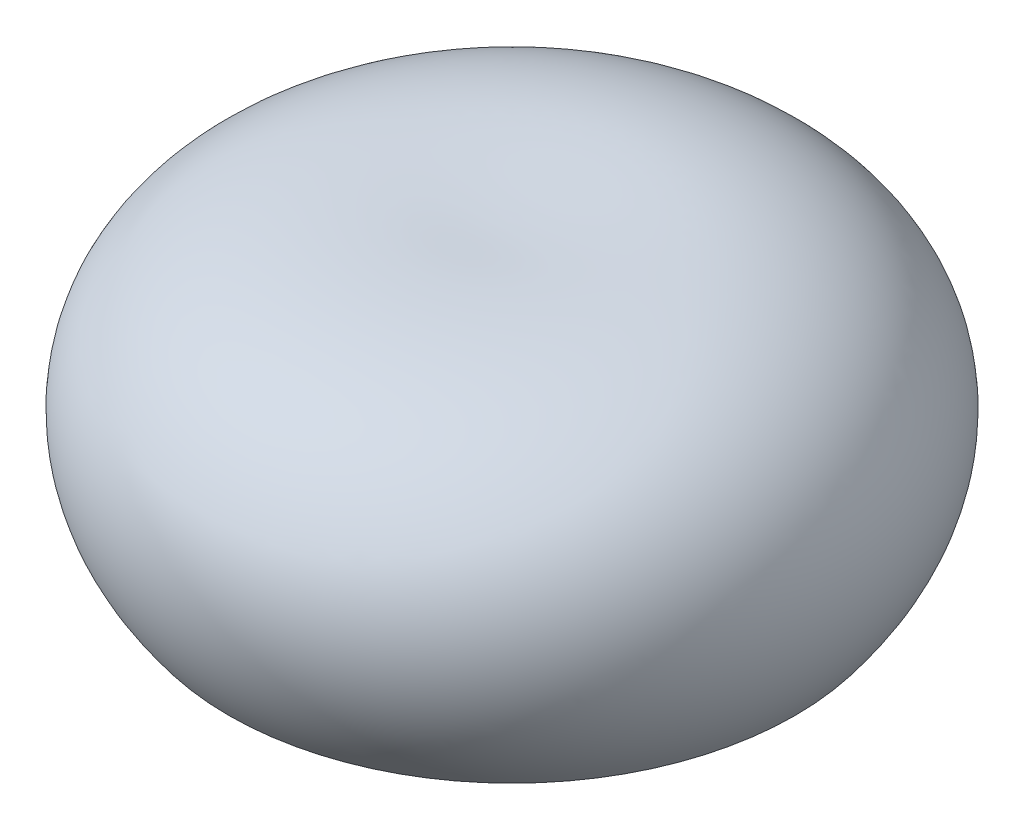
SolidWorks part; units mm, degrees
ref_plane "前视基准面" through (0, 0, 0) normal (0, 0, 1) x (1, 0, 0)
ref_plane "上视基准面" through (0, 0, 0) normal (0, 1, 0) x (1, 0, 0)
ref_plane "右视基准面" through (0, 0, 0) normal (1, 0, 0) x (0, 0, -1)
curve "曲线1"
  spline degree 3 poles (0, 7, 0) (0.0738, 6.9996, 0) (0.1783, 6.9991, 0) (0.3064, 7.0012, 0) (0.3805, 7.0029, 0) (0.4416, 7.0045, 0) (0.495, 7.0061, 0) (0.5432, 7.0077, 0) (0.5875, 7.0093, 0) (0.6288, 7.0109, 0) (0.6676, 7.0125, 0) (0.7044, 7.0141, 0) (0.7394, 7.0157, 0) (0.7729, 7.0172, 0) (0.8051, 7.0187, 0) (0.8362, 7.0203, 0) (0.8662, 7.0218, 0) (0.8953, 7.0233, 0) (0.9235, 7.0247, 0) (0.951, 7.0262, 0) (0.9778, 7.0276, 0) (1.004, 7.0291, 0) (1.0295, 7.0305, 0) (1.0545, 7.0319, 0) (1.079, 7.0333, 0) (1.103, 7.0346, 0) (1.1265, 7.036, 0) (1.1496, 7.0373, 0) (1.1724, 7.0386, 0) (1.1947, 7.0399, 0) (1.2167, 7.0412, 0) (1.2384, 7.0425, 0) (1.2598, 7.0438, 0) (1.2808, 7.045, 0) (1.3016, 7.0462, 0) (1.3221, 7.0474, 0) (1.3423, 7.0486, 0) (1.3623, 7.0498, 0) (1.382, 7.051, 0) (1.4015, 7.0521, 0) (1.4208, 7.0533, 0) (1.4399, 7.0544, 0) (1.4588, 7.0555, 0) (1.4775, 7.0566, 0) (1.496, 7.0577, 0) (1.5143, 7.0587, 0) (1.5324, 7.0598, 0) (1.5504, 7.0608, 0) (1.5682, 7.0618, 0) (1.5859, 7.0628, 0) (1.6034, 7.0638, 0) (1.6207, 7.0648, 0) (1.6379, 7.0657, 0) (1.655, 7.0667, 0) (1.672, 7.0676, 0) (1.6888, 7.0685, 0) (1.7054, 7.0694, 0) (1.722, 7.0703, 0) (1.7385, 7.0712, 0) (1.7548, 7.072, 0) (1.771, 7.0728, 0) (1.7871, 7.0737, 0) (1.8031, 7.0745, 0) (1.819, 7.0753, 0) (1.8348, 7.0761, 0) (1.8505, 7.0768, 0) (1.8661, 7.0776, 0) (1.8816, 7.0783, 0) (1.897, 7.079, 0) (1.9123, 7.0797, 0) (1.9275, 7.0804, 0) (1.9427, 7.0811, 0) (1.9578, 7.0818, 0) (1.9727, 7.0824, 0) (1.9876, 7.0831, 0) (2.0025, 7.0837, 0) (2.0172, 7.0843, 0) (2.0319, 7.0849, 0) (2.0465, 7.0855, 0) (2.061, 7.0861, 0) (2.0755, 7.0866, 0) (2.0899, 7.0872, 0) (2.1042, 7.0877, 0) (2.1184, 7.0882, 0) (2.1326, 7.0887, 0) (2.1468, 7.0892, 0) (2.1608, 7.0896, 0) (2.1748, 7.0901, 0) (2.1888, 7.0905, 0) (2.2027, 7.091, 0) (2.2165, 7.0914, 0) (2.2302, 7.0918, 0) (2.244, 7.0922, 0) (2.2576, 7.0925, 0) (2.2712, 7.0929, 0) (2.2848, 7.0933, 0) (2.2983, 7.0936, 0) (2.3117, 7.0939, 0) (2.3251, 7.0942, 0) (2.3385, 7.0945, 0) (2.3518, 7.0948, 0) (2.365, 7.095, 0) (2.3782, 7.0953, 0) (2.3914, 7.0955, 0) (2.4045, 7.0958, 0) (2.4175, 7.096, 0) (2.4305, 7.0962, 0) (2.4435, 7.0964, 0) (2.4565, 7.0965, 0) (2.4693, 7.0967, 0) (2.4822, 7.0968, 0) (2.495, 7.097, 0) (2.5078, 7.0971, 0) (2.5205, 7.0972, 0) (2.5332, 7.0973, 0) (2.5458, 7.0974, 0) (2.5584, 7.0974, 0) (2.571, 7.0975, 0) (2.5835, 7.0975, 0) (2.596, 7.0975, 0) (2.6085, 7.0975, 0) (2.6209, 7.0975, 0) (2.6333, 7.0975, 0) (2.6457, 7.0975, 0) (2.658, 7.0975, 0) (2.6703, 7.0974, 0) (2.6825, 7.0973, 0) (2.6948, 7.0973, 0) (2.7069, 7.0972, 0) (2.7191, 7.0971, 0) (2.7312, 7.0969, 0) (2.7433, 7.0968, 0) (2.7554, 7.0967, 0) (2.7674, 7.0965, 0) (2.7794, 7.0963, 0) (2.7914, 7.0962, 0) (2.8033, 7.096, 0) (2.8152, 7.0958, 0) (2.8271, 7.0955, 0) (2.8389, 7.0953, 0) (2.8508, 7.095, 0) (2.8625, 7.0948, 0) (2.8743, 7.0945, 0) (2.8861, 7.0942, 0) (2.8978, 7.0939, 0) (2.9094, 7.0936, 0) (2.9211, 7.0933, 0) (2.9327, 7.093, 0) (2.9443, 7.0926, 0) (2.9559, 7.0922, 0) (2.9675, 7.0919, 0) (2.979, 7.0915, 0) (2.9905, 7.0911, 0) (3.002, 7.0907, 0) (3.0134, 7.0902, 0) (3.0249, 7.0898, 0) (3.0363, 7.0893, 0) (3.0477, 7.0889, 0) (3.059, 7.0884, 0) (3.0704, 7.0879, 0) (3.0817, 7.0874, 0) (3.093, 7.0869, 0) (3.1042, 7.0864, 0) (3.1155, 7.0858, 0) (3.1267, 7.0853, 0) (3.1379, 7.0847, 0) (3.1491, 7.0841, 0) (3.1602, 7.0835, 0) (3.1714, 7.0829, 0) (3.1825, 7.0823, 0) (3.1936, 7.0817, 0) (3.2047, 7.0811, 0) (3.2157, 7.0804, 0) (3.2267, 7.0797, 0) (3.2378, 7.0791, 0) (3.2488, 7.0784, 0) (3.2597, 7.0777, 0) (3.2707, 7.0769, 0) (3.2816, 7.0762, 0) (3.2925, 7.0755, 0) (3.3034, 7.0747, 0) (3.3143, 7.074, 0) (3.3252, 7.0732, 0) (3.336, 7.0724, 0) (3.3468, 7.0716, 0) (3.3576, 7.0708, 0) (3.3684, 7.0699, 0) (3.3792, 7.0691, 0) (3.3899, 7.0683, 0) (3.4006, 7.0674, 0) (3.4113, 7.0665, 0) (3.422, 7.0656, 0) (3.4327, 7.0647, 0) (3.4434, 7.0638, 0) (3.454, 7.0629, 0) (3.4646, 7.0619, 0) (3.4752, 7.061, 0) (3.4858, 7.06, 0) (3.4964, 7.059, 0) (3.507, 7.0581, 0) (3.5175, 7.0571, 0) (3.528, 7.056, 0) (3.5385, 7.055, 0) (3.549, 7.054, 0) (3.5595, 7.0529, 0) (3.5699, 7.0519, 0) (3.5804, 7.0508, 0) (3.5908, 7.0497, 0) (3.6012, 7.0486, 0) (3.6116, 7.0475, 0) (3.622, 7.0464, 0) (3.6324, 7.0452, 0) (3.6427, 7.0441, 0) (3.6531, 7.0429, 0) (3.6634, 7.0417, 0) (3.6737, 7.0406, 0) (3.684, 7.0394, 0) (3.6942, 7.0381, 0) (3.7045, 7.0369, 0) (3.7148, 7.0357, 0) (3.725, 7.0344, 0) (3.7352, 7.0332, 0) (3.7454, 7.0319, 0) (3.7556, 7.0306, 0) (3.7658, 7.0293, 0) (3.7759, 7.028, 0) (3.7861, 7.0267, 0) (3.7962, 7.0254, 0) (3.8063, 7.024, 0) (3.8164, 7.0227, 0) (3.8265, 7.0213, 0) (3.8366, 7.0199, 0) (3.8467, 7.0185, 0) (3.8567, 7.0171, 0) (3.8668, 7.0157, 0) (3.8768, 7.0142, 0) (3.8868, 7.0128, 0) (3.8968, 7.0113, 0) (3.9068, 7.0099, 0) (3.9168, 7.0084, 0) (3.9267, 7.0069, 0) (3.9367, 7.0054, 0) (3.9466, 7.0039, 0) (3.9565, 7.0024, 0) (3.9665, 7.0008, 0) (3.9764, 6.9993, 0) (3.9862, 6.9977, 0) (3.9961, 6.9961, 0) (4.006, 6.9945, 0) (4.0158, 6.9929, 0) (4.0257, 6.9913, 0) (4.0355, 6.9897, 0) (4.0453, 6.988, 0) (4.0551, 6.9864, 0) (4.0649, 6.9847, 0) (4.0747, 6.983, 0) (4.0844, 6.9813, 0) (4.0942, 6.9796, 0) (4.1039, 6.9779, 0) (4.1136, 6.9762, 0) (4.1234, 6.9745, 0) (4.1331, 6.9727, 0) (4.1428, 6.971, 0) (4.1524, 6.9692, 0) (4.1621, 6.9674, 0) (4.1718, 6.9656, 0) (4.1814, 6.9638, 0) (4.1911, 6.962, 0) (4.2007, 6.9601, 0) (4.2103, 6.9583, 0) (4.2199, 6.9564, 0) (4.2295, 6.9545, 0) (4.2391, 6.9527, 0) (4.2486, 6.9508, 0) (4.2582, 6.9488, 0) (4.2677, 6.9469, 0) (4.2773, 6.945, 0) (4.2868, 6.943, 0) (4.2963, 6.9411, 0) (4.3058, 6.9391, 0) (4.3153, 6.9371, 0) (4.3248, 6.9351, 0) (4.3343, 6.9331, 0) (4.3437, 6.9311, 0) (4.3532, 6.9291, 0) (4.3626, 6.927, 0) (4.3721, 6.925, 0) (4.3815, 6.9229, 0) (4.3909, 6.9208, 0) (4.4003, 6.9187, 0) (4.4097, 6.9166, 0) (4.4191, 6.9145, 0) (4.4284, 6.9123, 0) (4.4378, 6.9102, 0) (4.4471, 6.908, 0) (4.4565, 6.9059, 0) (4.4658, 6.9037, 0) (4.4751, 6.9015, 0) (4.4844, 6.8993, 0) (4.4937, 6.8971, 0) (4.503, 6.8948, 0) (4.5123, 6.8926, 0) (4.5215, 6.8903, 0) (4.5308, 6.8881, 0) (4.54, 6.8858, 0) (4.5493, 6.8835, 0) (4.5585, 6.8812, 0) (4.5677, 6.8789, 0) (4.5769, 6.8765, 0) (4.5861, 6.8742, 0) (4.5953, 6.8718, 0) (4.6045, 6.8695, 0) (4.6136, 6.8671, 0) (4.6228, 6.8647, 0) (4.6319, 6.8623, 0) (4.6411, 6.8599, 0) (4.6502, 6.8575, 0) (4.6593, 6.855, 0) (4.6684, 6.8526, 0) (4.6775, 6.8501, 0) (4.6866, 6.8476, 0) (4.6957, 6.8451, 0) (4.7048, 6.8426, 0) (4.7138, 6.8401, 0) (4.7229, 6.8376, 0) (4.7319, 6.835, 0) (4.741, 6.8325, 0) (4.75, 6.8299, 0) (4.759, 6.8273, 0) (4.768, 6.8247, 0) (4.777, 6.8221, 0) (4.786, 6.8195, 0) (4.795, 6.8169, 0) (4.8039, 6.8142, 0) (4.8129, 6.8116, 0) (4.8218, 6.8089, 0) (4.8308, 6.8062, 0) (4.8397, 6.8035, 0) (4.8486, 6.8008, 0) (4.8575, 6.7981, 0) (4.8664, 6.7954, 0) (4.8753, 6.7926, 0) (4.8842, 6.7899, 0) (4.8931, 6.7871, 0) (4.902, 6.7843, 0) (4.9108, 6.7815, 0) (4.9197, 6.7787, 0) (4.9285, 6.7759, 0) (4.9373, 6.7731, 0) (4.9462, 6.7702, 0) (4.955, 6.7673, 0) (4.9638, 6.7645, 0) (4.9726, 6.7616, 0) (4.9813, 6.7587, 0) (4.9901, 6.7558, 0) (4.9989, 6.7529, 0) (5.0076, 6.7499, 0) (5.0164, 6.747, 0) (5.0251, 6.744, 0) (5.0339, 6.7411, 0) (5.0426, 6.7381, 0) (5.0513, 6.7351, 0) (5.06, 6.7321, 0) (5.0687, 6.729, 0) (5.0774, 6.726, 0) (5.0861, 6.7229, 0) (5.0947, 6.7199, 0) (5.1034, 6.7168, 0) (5.112, 6.7137, 0) (5.1207, 6.7106, 0) (5.1293, 6.7075, 0) (5.1379, 6.7044, 0) (5.1465, 6.7012, 0) (5.1552, 6.6981, 0) (5.1638, 6.6949, 0) (5.1723, 6.6917, 0) (5.1809, 6.6885, 0) (5.1895, 6.6853, 0) (5.1981, 6.6821, 0) (5.2066, 6.6789, 0) (5.2151, 6.6756, 0) (5.2237, 6.6724, 0) (5.2322, 6.6691, 0) (5.2407, 6.6658, 0) (5.2492, 6.6625, 0) (5.2577, 6.6592, 0) (5.2662, 6.6559, 0) (5.2747, 6.6526, 0) (5.2832, 6.6492, 0) (5.2917, 6.6459, 0) (5.3001, 6.6425, 0) (5.3086, 6.6391, 0) (5.317, 6.6357, 0) (5.3254, 6.6323, 0) (5.3338, 6.6289, 0) (5.3423, 6.6254, 0) (5.3507, 6.622, 0) (5.3591, 6.6185, 0) (5.3674, 6.615, 0) (5.3758, 6.6115, 0) (5.3842, 6.608, 0) (5.3926, 6.6045, 0) (5.4009, 6.601, 0) (5.4092, 6.5974, 0) (5.4176, 6.5939, 0) (5.4259, 6.5903, 0) (5.4342, 6.5867, 0) (5.4425, 6.5831, 0) (5.4508, 6.5795, 0) (5.4591, 6.5759, 0) (5.4674, 6.5722, 0) (5.4757, 6.5686, 0) (5.4839, 6.5649, 0) (5.4922, 6.5612, 0) (5.5004, 6.5576, 0) (5.5087, 6.5538, 0) (5.5169, 6.5501, 0) (5.5251, 6.5464, 0) (5.5333, 6.5427, 0) (5.5415, 6.5389, 0) (5.5497, 6.5351, 0) (5.5579, 6.5313, 0) (5.5661, 6.5275, 0) (5.5743, 6.5237, 0) (5.5824, 6.5199, 0) (5.5906, 6.5161, 0) (5.5987, 6.5122, 0) (5.6069, 6.5083, 0) (5.615, 6.5045, 0) (5.6231, 6.5006, 0) (5.6312, 6.4967, 0) (5.6393, 6.4927, 0) (5.6474, 6.4888, 0) (5.6555, 6.4849, 0) (5.6635, 6.4809, 0) (5.6716, 6.4769, 0) (5.6796, 6.4729, 0) (5.6877, 6.4689, 0) (5.6957, 6.4649, 0) (5.7038, 6.4609, 0) (5.7118, 6.4568, 0) (5.7198, 6.4528, 0) (5.7278, 6.4487, 0) (5.7358, 6.4446, 0) (5.7438, 6.4405, 0) (5.7517, 6.4364, 0) (5.7597, 6.4323, 0) (5.7676, 6.4282, 0) (5.7756, 6.424, 0) (5.7835, 6.4198, 0) (5.7915, 6.4157, 0) (5.7994, 6.4115, 0) (5.8073, 6.4073, 0) (5.8152, 6.403, 0) (5.8231, 6.3988, 0) (5.831, 6.3945, 0) (5.8388, 6.3903, 0) (5.8467, 6.386, 0) (5.8546, 6.3817, 0) (5.8624, 6.3774, 0) (5.8703, 6.3731, 0) (5.8781, 6.3687, 0) (5.8859, 6.3644, 0) (5.8937, 6.36, 0) (5.9015, 6.3557, 0) (5.9093, 6.3513, 0) (5.9171, 6.3469, 0) (5.9249, 6.3424, 0) (5.9326, 6.338, 0) (5.9404, 6.3336, 0) (5.9481, 6.3291, 0) (5.9559, 6.3246, 0) (5.9636, 6.3201, 0) (5.9713, 6.3156, 0) (5.979, 6.3111, 0) (5.9867, 6.3066, 0) (5.9944, 6.302, 0) (6.0021, 6.2975, 0) (6.0098, 6.2929, 0) (6.0175, 6.2883, 0) (6.0251, 6.2837, 0) (6.0328, 6.2791, 0) (6.0404, 6.2745, 0) (6.048, 6.2698, 0) (6.0556, 6.2652, 0) (6.0633, 6.2605, 0) (6.0709, 6.2558, 0) (6.0784, 6.2511, 0) (6.086, 6.2464, 0) (6.0936, 6.2416, 0) (6.1012, 6.2369, 0) (6.1087, 6.2321, 0) (6.1163, 6.2274, 0) (6.1238, 6.2226, 0) (6.1313, 6.2178, 0) (6.1388, 6.2129, 0) (6.1463, 6.2081, 0) (6.1538, 6.2033, 0) (6.1613, 6.1984, 0) (6.1688, 6.1935, 0) (6.1763, 6.1886, 0) (6.1837, 6.1837, 0) (6.1912, 6.1788, 0) (6.1986, 6.1739, 0) (6.206, 6.1689, 0) (6.2134, 6.1639, 0) (6.2208, 6.159, 0) (6.2282, 6.154, 0) (6.2356, 6.1489, 0) (6.243, 6.1439, 0) (6.2504, 6.1389, 0) (6.2577, 6.1338, 0) (6.2651, 6.1287, 0) (6.2724, 6.1237, 0) (6.2798, 6.1186, 0) (6.2871, 6.1134, 0) (6.2944, 6.1083, 0) (6.3017, 6.1032, 0) (6.309, 6.098, 0) (6.3163, 6.0928, 0) (6.3235, 6.0876, 0) (6.3308, 6.0824, 0) (6.3381, 6.0772, 0) (6.3453, 6.072, 0) (6.3525, 6.0667, 0) (6.3598, 6.0615, 0) (6.367, 6.0562, 0) (6.3742, 6.0509, 0) (6.3814, 6.0456, 0) (6.3885, 6.0403, 0) (6.3957, 6.0349, 0) (6.4029, 6.0296, 0) (6.41, 6.0242, 0) (6.4172, 6.0188, 0) (6.4243, 6.0134, 0) (6.4314, 6.008, 0) (6.4385, 6.0025, 0) (6.4456, 5.9971, 0) (6.4527, 5.9916, 0) (6.4598, 5.9861, 0) (6.4668, 5.9806, 0) (6.4739, 5.9751, 0) (6.4809, 5.9696, 0) (6.488, 5.9641, 0) (6.495, 5.9585, 0) (6.502, 5.9529, 0) (6.509, 5.9473, 0) (6.516, 5.9417, 0) (6.523, 5.9361, 0) (6.53, 5.9305, 0) (6.5369, 5.9248, 0) (6.5439, 5.9192, 0) (6.5508, 5.9135, 0) (6.5578, 5.9078, 0) (6.5647, 5.9021, 0) (6.5716, 5.8963, 0) (6.5785, 5.8906, 0) (6.5854, 5.8848, 0) (6.5922, 5.8791, 0) (6.5991, 5.8733, 0) (6.606, 5.8675, 0) (6.6128, 5.8616, 0) (6.6196, 5.8558, 0) (6.6265, 5.8499, 0) (6.6333, 5.8441, 0) (6.6401, 5.8382, 0) (6.6469, 5.8323, 0) (6.6536, 5.8263, 0) (6.6604, 5.8204, 0) (6.6672, 5.8144, 0) (6.6739, 5.8085, 0) (6.6806, 5.8025, 0) (6.6874, 5.7965, 0) (6.6941, 5.7905, 0) (6.7008, 5.7844, 0) (6.7074, 5.7784, 0) (6.7141, 5.7723, 0) (6.7208, 5.7662, 0) (6.7274, 5.7601, 0) (6.7341, 5.754, 0) (6.7407, 5.7479, 0) (6.7473, 5.7417, 0) (6.7539, 5.7356, 0) (6.7605, 5.7294, 0) (6.7671, 5.7232, 0) (6.7737, 5.717, 0) (6.7802, 5.7107, 0) (6.7868, 5.7045, 0) (6.7933, 5.6982, 0) (6.7998, 5.6919, 0) (6.8064, 5.6856, 0) (6.8129, 5.6793, 0) (6.8194, 5.673, 0) (6.8258, 5.6666, 0) (6.8323, 5.6603, 0) (6.8387, 5.6539, 0) (6.8452, 5.6475, 0) (6.8516, 5.6411, 0) (6.858, 5.6346, 0) (6.8644, 5.6282, 0) (6.8708, 5.6217, 0) (6.8772, 5.6152, 0) (6.8836, 5.6087, 0) (6.8899, 5.6022, 0) (6.8963, 5.5957, 0) (6.9026, 5.5891, 0) (6.9089, 5.5825, 0) (6.9152, 5.5759, 0) (6.9215, 5.5693, 0) (6.9278, 5.5627, 0) (6.9341, 5.5561, 0) (6.9403, 5.5494, 0) (6.9466, 5.5427, 0) (6.9528, 5.5361, 0) (6.959, 5.5293, 0) (6.9652, 5.5226, 0) (6.9714, 5.5159, 0) (6.9776, 5.5091, 0) (6.9838, 5.5023, 0) (6.9899, 5.4955, 0) (6.9961, 5.4887, 0) (7.0022, 5.4819, 0) (7.0083, 5.475, 0) (7.0144, 5.4682, 0) (7.0205, 5.4613, 0) (7.0266, 5.4544, 0) (7.0326, 5.4475, 0) (7.0387, 5.4405, 0) (7.0447, 5.4336, 0) (7.0507, 5.4266, 0) (7.0568, 5.4196, 0) (7.0627, 5.4126, 0) (7.0687, 5.4055, 0) (7.0747, 5.3985, 0) (7.0807, 5.3914, 0) (7.0866, 5.3844, 0) (7.0925, 5.3772, 0) (7.0984, 5.3701, 0) (7.1043, 5.363, 0) (7.1102, 5.3558, 0) (7.1161, 5.3487, 0) (7.122, 5.3415, 0) (7.1278, 5.3343, 0) (7.1336, 5.327, 0) (7.1395, 5.3198, 0) (7.1453, 5.3125, 0) (7.151, 5.3052, 0) (7.1568, 5.2979, 0) (7.1626, 5.2906, 0) (7.1683, 5.2833, 0) (7.1741, 5.2759, 0) (7.1798, 5.2685, 0) (7.1855, 5.2611, 0) (7.1912, 5.2537, 0) (7.1968, 5.2463, 0) (7.2025, 5.2388, 0) (7.2082, 5.2313, 0) (7.2138, 5.2238, 0) (7.2194, 5.2163, 0) (7.225, 5.2088, 0) (7.2306, 5.2013, 0) (7.2362, 5.1937, 0) (7.2417, 5.1861, 0) (7.2473, 5.1785, 0) (7.2528, 5.1709, 0) (7.2583, 5.1632, 0) (7.2638, 5.1556, 0) (7.2693, 5.1479, 0) (7.2748, 5.1402, 0) (7.2802, 5.1324, 0) (7.2856, 5.1247, 0) (7.2911, 5.1169, 0) (7.2965, 5.1092, 0) (7.3019, 5.1014, 0) (7.3072, 5.0935, 0) (7.3126, 5.0857, 0) (7.3179, 5.0778, 0) (7.3233, 5.0699, 0) (7.3286, 5.062, 0) (7.3339, 5.0541, 0) (7.3391, 5.0462, 0) (7.3444, 5.0382, 0) (7.3497, 5.0302, 0) (7.3549, 5.0222, 0) (7.3601, 5.0142, 0) (7.3653, 5.0062, 0) (7.3705, 4.9981, 0) (7.3757, 4.99, 0) (7.3808, 4.9819, 0) (7.3859, 4.9738, 0) (7.3911, 4.9657, 0) (7.3962, 4.9575, 0) (7.4012, 4.9493, 0) (7.4063, 4.9411, 0) (7.4114, 4.9329, 0) (7.4164, 4.9246, 0) (7.4214, 4.9164, 0) (7.4264, 4.9081, 0) (7.4314, 4.8998, 0) (7.4364, 4.8914, 0) (7.4413, 4.8831, 0) (7.4462, 4.8747, 0) (7.4512, 4.8663, 0) (7.4561, 4.8579, 0) (7.4609, 4.8495, 0) (7.4658, 4.841, 0) (7.4706, 4.8325, 0) (7.4755, 4.824, 0) (7.4803, 4.8155, 0) (7.4851, 4.807, 0) (7.4899, 4.7984, 0) (7.4946, 4.7898, 0) (7.4993, 4.7812, 0) (7.5041, 4.7726, 0) (7.5088, 4.7639, 0) (7.5134, 4.7552, 0) (7.5181, 4.7465, 0) (7.5228, 4.7378, 0) (7.5274, 4.7291, 0) (7.532, 4.7203, 0) (7.5366, 4.7115, 0) (7.5412, 4.7027, 0) (7.5457, 4.6939, 0) (7.5503, 4.6851, 0) (7.5548, 4.6762, 0) (7.5593, 4.6673, 0) (7.5637, 4.6584, 0) (7.5682, 4.6494, 0) (7.5726, 4.6405, 0) (7.5771, 4.6315, 0) (7.5815, 4.6225, 0) (7.5858, 4.6134, 0) (7.5902, 4.6044, 0) (7.5945, 4.5953, 0) (7.5989, 4.5862, 0) (7.6032, 4.5771, 0) (7.6075, 4.5679, 0) (7.6117, 4.5587, 0) (7.616, 4.5495, 0) (7.6202, 4.5403, 0) (7.6244, 4.5311, 0) (7.6286, 4.5218, 0) (7.6327, 4.5125, 0) (7.6369, 4.5032, 0) (7.641, 4.4939, 0) (7.6451, 4.4845, 0) (7.6492, 4.4751, 0) (7.6532, 4.4657, 0) (7.6573, 4.4563, 0) (7.6613, 4.4468, 0) (7.6653, 4.4373, 0) (7.6692, 4.4278, 0) (7.6732, 4.4183, 0) (7.6771, 4.4087, 0) (7.681, 4.3992, 0) (7.6849, 4.3896, 0) (7.6888, 4.3799, 0) (7.6926, 4.3703, 0) (7.6964, 4.3606, 0) (7.7002, 4.3509, 0) (7.704, 4.3411, 0) (7.7078, 4.3314, 0) (7.7115, 4.3216, 0) (7.7152, 4.3118, 0) (7.7189, 4.302, 0) (7.7226, 4.2921, 0) (7.7262, 4.2822, 0) (7.7298, 4.2723, 0) (7.7334, 4.2624, 0) (7.737, 4.2524, 0) (7.7405, 4.2424, 0) (7.744, 4.2324, 0) (7.7475, 4.2223, 0) (7.751, 4.2123, 0) (7.7545, 4.2022, 0) (7.7579, 4.1921, 0) (7.7613, 4.1819, 0) (7.7647, 4.1717, 0) (7.768, 4.1615, 0) (7.7714, 4.1513, 0) (7.7747, 4.141, 0) (7.778, 4.1308, 0) (7.7812, 4.1204, 0) (7.7845, 4.1101, 0) (7.7877, 4.0997, 0) (7.7908, 4.0893, 0) (7.794, 4.0789, 0) (7.7971, 4.0685, 0) (7.8002, 4.058, 0) (7.8033, 4.0475, 0) (7.8064, 4.0369, 0) (7.8094, 4.0264, 0) (7.8124, 4.0158, 0) (7.8154, 4.0051, 0) (7.8183, 3.9945, 0) (7.8212, 3.9838, 0) (7.8241, 3.9731, 0) (7.827, 3.9624, 0) (7.8298, 3.9516, 0) (7.8327, 3.9408, 0) (7.8354, 3.93, 0) (7.8382, 3.9191, 0) (7.8409, 3.9082, 0) (7.8436, 3.8973, 0) (7.8463, 3.8863, 0) (7.849, 3.8754, 0) (7.8516, 3.8643, 0) (7.8542, 3.8533, 0) (7.8567, 3.8422, 0) (7.8593, 3.8311, 0) (7.8618, 3.82, 0) (7.8642, 3.8088, 0) (7.8667, 3.7976, 0) (7.8691, 3.7864, 0) (7.8715, 3.7751, 0) (7.8738, 3.7638, 0) (7.8762, 3.7525, 0) (7.8785, 3.7411, 0) (7.8807, 3.7297, 0) (7.883, 3.7183, 0) (7.8852, 3.7069, 0) (7.8873, 3.6954, 0) (7.8895, 3.6838, 0) (7.8916, 3.6723, 0) (7.8937, 3.6607, 0) (7.8957, 3.6491, 0) (7.8977, 3.6374, 0) (7.8997, 3.6257, 0) (7.9016, 3.614, 0) (7.9036, 3.6022, 0) (7.9054, 3.5904, 0) (7.9073, 3.5786, 0) (7.9091, 3.5667, 0) (7.9109, 3.5548, 0) (7.9126, 3.5429, 0) (7.9144, 3.5309, 0) (7.916, 3.5189, 0) (7.9177, 3.5068, 0) (7.9193, 3.4947, 0) (7.9209, 3.4826, 0) (7.9224, 3.4705, 0) (7.9239, 3.4583, 0) (7.9254, 3.446, 0) (7.9268, 3.4338, 0) (7.9282, 3.4214, 0) (7.9296, 3.4091, 0) (7.9309, 3.3967, 0) (7.9322, 3.3843, 0) (7.9334, 3.3718, 0) (7.9346, 3.3593, 0) (7.9358, 3.3468, 0) (7.9369, 3.3342, 0) (7.938, 3.3215, 0) (7.9391, 3.3089, 0) (7.9401, 3.2962, 0) (7.9411, 3.2834, 0) (7.942, 3.2706, 0) (7.9429, 3.2578, 0) (7.9438, 3.2449, 0) (7.9446, 3.232, 0) (7.9454, 3.219, 0) (7.9461, 3.206, 0) (7.9468, 3.193, 0) (7.9475, 3.1799, 0) (7.9481, 3.1668, 0) (7.9486, 3.1536, 0) (7.9492, 3.1403, 0) (7.9496, 3.1271, 0) (7.9501, 3.1138, 0) (7.9505, 3.1004, 0) (7.9508, 3.087, 0) (7.9511, 3.0735, 0) (7.9514, 3.06, 0) (7.9516, 3.0465, 0) (7.9517, 3.0329, 0) (7.9518, 3.0192, 0) (7.9519, 3.0055, 0) (7.9519, 2.9918, 0) (7.9519, 2.978, 0) (7.9518, 2.9641, 0) (7.9517, 2.9502, 0) (7.9515, 2.9363, 0) (7.9513, 2.9223, 0) (7.951, 2.9082, 0) (7.9507, 2.8941, 0) (7.9503, 2.88, 0) (7.9499, 2.8657, 0) (7.9494, 2.8515, 0) (7.9489, 2.8371, 0) (7.9483, 2.8228, 0) (7.9477, 2.8083, 0) (7.947, 2.7938, 0) (7.9462, 2.7793, 0) (7.9454, 2.7647, 0) (7.9445, 2.75, 0) (7.9436, 2.7353, 0) (7.9426, 2.7205, 0) (7.9416, 2.7056, 0) (7.9405, 2.6907, 0) (7.9393, 2.6757, 0) (7.9381, 2.6607, 0) (7.9368, 2.6456, 0) (7.9355, 2.6304, 0) (7.9341, 2.6152, 0) (7.9326, 2.5999, 0) (7.9311, 2.5845, 0) (7.9295, 2.5691, 0) (7.9278, 2.5536, 0) (7.9261, 2.538, 0) (7.9243, 2.5224, 0) (7.9224, 2.5066, 0) (7.9205, 2.4909, 0) (7.9185, 2.475, 0) (7.9164, 2.459, 0) (7.9143, 2.443, 0) (7.912, 2.4269, 0) (7.9097, 2.4108, 0) (7.9074, 2.3945, 0) (7.9049, 2.3782, 0) (7.9024, 2.3618, 0) (7.8998, 2.3453, 0) (7.8971, 2.3287, 0) (7.8943, 2.312, 0) (7.8915, 2.2953, 0) (7.8885, 2.2784, 0) (7.8855, 2.2615, 0) (7.8824, 2.2445, 0) (7.8792, 2.2273, 0) (7.8759, 2.2101, 0) (7.8725, 2.1928, 0) (7.8691, 2.1754, 0) (7.8655, 2.1579, 0) (7.8618, 2.1403, 0) (7.8581, 2.1225, 0) (7.8542, 2.1047, 0) (7.8503, 2.0868, 0) (7.8462, 2.0687, 0) (7.842, 2.0506, 0) (7.8378, 2.0323, 0) (7.8334, 2.0139, 0) (7.8289, 1.9954, 0) (7.8243, 1.9767, 0) (7.8195, 1.9579, 0) (7.8147, 1.939, 0) (7.8097, 1.92, 0) (7.8046, 1.9008, 0) (7.7994, 1.8815, 0) (7.794, 1.8621, 0) (7.7885, 1.8425, 0) (7.7829, 1.8227, 0) (7.7771, 1.8028, 0) (7.7712, 1.7828, 0) (7.7652, 1.7626, 0) (7.759, 1.7422, 0) (7.7526, 1.7216, 0) (7.7461, 1.7009, 0) (7.7394, 1.6799, 0) (7.7325, 1.6588, 0) (7.7255, 1.6375, 0) (7.7182, 1.616, 0) (7.7108, 1.5943, 0) (7.7032, 1.5723, 0) (7.6954, 1.5502, 0) (7.6874, 1.5278, 0) (7.6792, 1.5051, 0) (7.6708, 1.4822, 0) (7.6621, 1.4591, 0) (7.6532, 1.4357, 0) (7.644, 1.412, 0) (7.6346, 1.388, 0) (7.6249, 1.3637, 0) (7.615, 1.3391, 0) (7.6047, 1.3141, 0) (7.5941, 1.2888, 0) (7.5833, 1.2631, 0) (7.572, 1.237, 0) (7.5604, 1.2105, 0) (7.5485, 1.1835, 0) (7.5361, 1.1561, 0) (7.5233, 1.1282, 0) (7.51, 1.0997, 0) (7.4963, 1.0707, 0) (7.482, 1.041, 0) (7.4672, 1.0107, 0) (7.4518, 0.9797, 0) (7.4357, 0.9478, 0) (7.4189, 0.9152, 0) (7.4013, 0.8815, 0) (7.3829, 0.8469, 0) (7.3635, 0.811, 0) (7.343, 0.7739, 0) (7.3212, 0.7352, 0) (7.2981, 0.6948, 0) (7.2732, 0.6523, 0) (7.2464, 0.6073, 0) (7.2172, 0.5594, 0) (7.1849, 0.5076, 0) (7.1485, 0.4506, 0) (7.1062, 0.386, 0) (7.0539, 0.3086, 0) (6.9626, 0.1779, 0) (6.8856, 0.0734, 0) (6.8314, 0, 0) knots 0 0 0 0 0.016508 0.023364 0.028636 0.033092 0.037026 0.040591 0.043877 0.046942 0.049828 0.052563 0.055171 0.057668 0.060068 0.062382 0.06462 0.066789 0.068896 0.070946 0.072944 0.074894 0.0768 0.078664 0.080491 0.082282 0.08404 0.085766 0.087463 0.089131 0.090774 0.092392 0.093986 0.095557 0.097107 0.098637 0.100147 0.101639 0.103112 0.104569 0.10601 0.107434 0.108844 0.110239 0.11162 0.112987 0.114341 0.115683 0.117013 0.118331 0.119637 0.120933 0.122218 0.123492 0.124757 0.126012 0.127257 0.128493 0.129721 0.130939 0.132149 0.133351 0.134545 0.135731 0.13691 0.138081 0.139245 0.140402 0.141552 0.142695 0.143832 0.144962 0.146086 0.147204 0.148315 0.149421 0.150522 0.151616 0.152705 0.153789 0.154868 0.155941 0.157009 0.158072 0.159131 0.160184 0.161233 0.162277 0.163317 0.164352 0.165383 0.16641 0.167433 0.168451 0.169465 0.170476 0.171482 0.172485 0.173483 0.174478 0.17547 0.176457 0.177442 0.178422 0.1794 0.180374 0.181344 0.182312 0.183276 0.184236 0.185194 0.186149 0.187101 0.188049 0.188995 0.189938 0.190877 0.191815 0.192749 0.19368 0.194609 0.195535 0.196459 0.19738 0.198298 0.199214 0.200127 0.201038 0.201946 0.202852 0.203756 0.204657 0.205556 0.206453 0.207347 0.208239 0.209129 0.210017 0.210902 0.211786 0.212667 0.213547 0.214424 0.215299 0.216172 0.217044 0.217913 0.21878 0.219646 0.220509 0.221371 0.222231 0.223089 0.223945 0.2248 0.225652 0.226503 0.227353 0.2282 0.229046 0.22989 0.230732 0.231573 0.232412 0.23325 0.234086 0.23492 0.235753 0.236585 0.237414 0.238243 0.239069 0.239895 0.240719 0.241541 0.242362 0.243182 0.244 0.244816 0.245632 0.246446 0.247258 0.24807 0.24888 0.249688 0.250496 0.251302 0.252106 0.25291 0.253712 0.254513 0.255313 0.256111 0.256909 0.257705 0.2585 0.259294 0.260086 0.260878 0.261668 0.262457 0.263245 0.264032 0.264818 0.265603 0.266386 0.267169 0.26795 0.268731 0.26951 0.270288 0.271066 0.271842 0.272617 0.273391 0.274165 0.274937 0.275708 0.276478 0.277248 0.278016 0.278784 0.27955 0.280316 0.28108 0.281844 0.282607 0.283369 0.28413 0.28489 0.285649 0.286407 0.287165 0.287921 0.288677 0.289432 0.290186 0.290939 0.291692 0.292444 0.293194 0.293944 0.294693 0.295442 0.296189 0.296936 0.297682 0.298428 0.299172 0.299916 0.300659 0.301401 0.302143 0.302883 0.303624 0.304363 0.305101 0.305839 0.306577 0.307313 0.308049 0.308784 0.309518 0.310252 0.310985 0.311718 0.312449 0.31318 0.313911 0.31464 0.31537 0.316098 0.316826 0.317553 0.31828 0.319006 0.319731 0.320456 0.32118 0.321903 0.322626 0.323349 0.32407 0.324791 0.325512 0.326232 0.326951 0.32767 0.328389 0.329106 0.329824 0.33054 0.331256 0.331972 0.332687 0.333401 0.334115 0.334829 0.335541 0.336254 0.336966 0.337677 0.338388 0.339098 0.339808 0.340517 0.341226 0.341934 0.342642 0.34335 0.344057 0.344763 0.345469 0.346174 0.346879 0.347584 0.348288 0.348992 0.349695 0.350398 0.3511 0.351802 0.352503 0.353204 0.353905 0.354605 0.355305 0.356004 0.356703 0.357401 0.3581 0.358797 0.359494 0.360191 0.360888 0.361584 0.362279 0.362975 0.36367 0.364364 0.365058 0.365752 0.366445 0.367138 0.367831 0.368523 0.369215 0.369907 0.370598 0.371289 0.371979 0.372669 0.373359 0.374049 0.374738 0.375427 0.376115 0.376803 0.377491 0.378178 0.378866 0.379552 0.380239 0.380925 0.381611 0.382297 0.382982 0.383667 0.384351 0.385036 0.38572 0.386404 0.387087 0.38777 0.388453 0.389136 0.389818 0.3905 0.391182 0.391863 0.392545 0.393226 0.393906 0.394587 0.395267 0.395947 0.396627 0.397306 0.397985 0.398664 0.399343 0.400021 0.400699 0.401377 0.402055 0.402733 0.40341 0.404087 0.404764 0.40544 0.406117 0.406793 0.407469 0.408144 0.40882 0.409495 0.41017 0.410845 0.41152 0.412194 0.412868 0.413542 0.414216 0.41489 0.415563 0.416237 0.41691 0.417583 0.418255 0.418928 0.4196 0.420273 0.420945 0.421616 0.422288 0.42296 0.423631 0.424302 0.424973 0.425644 0.426315 0.426986 0.427656 0.428326 0.428997 0.429667 0.430336 0.431006 0.431676 0.432345 0.433015 0.433684 0.434353 0.435022 0.435691 0.436359 0.437028 0.437696 0.438365 0.439033 0.439701 0.440369 0.441037 0.441705 0.442373 0.44304 0.443708 0.444375 0.445043 0.44571 0.446377 0.447044 0.447711 0.448378 0.449045 0.449711 0.450378 0.451045 0.451711 0.452378 0.453044 0.45371 0.454377 0.455043 0.455709 0.456375 0.457041 0.457707 0.458373 0.459039 0.459705 0.460371 0.461036 0.461702 0.462368 0.463034 0.463699 0.464365 0.46503 0.465696 0.466361 0.467027 0.467692 0.468358 0.469023 0.469689 0.470354 0.47102 0.471685 0.472351 0.473016 0.473681 0.474347 0.475012 0.475678 0.476343 0.477009 0.477674 0.47834 0.479005 0.479671 0.480336 0.481002 0.481668 0.482333 0.482999 0.483665 0.48433 0.484996 0.485662 0.486328 0.486994 0.48766 0.488326 0.488992 0.489658 0.490324 0.490991 0.491657 0.492324 0.49299 0.493657 0.494323 0.49499 0.495657 0.496324 0.496991 0.497658 0.498325 0.498992 0.499659 0.500327 0.500994 0.501662 0.50233 0.502997 0.503665 0.504333 0.505001 0.50567 0.506338 0.507007 0.507675 0.508344 0.509013 0.509682 0.510351 0.511021 0.51169 0.51236 0.513029 0.513699 0.514369 0.515039 0.51571 0.51638 0.517051 0.517722 0.518393 0.519064 0.519735 0.520407 0.521078 0.52175 0.522422 0.523095 0.523767 0.52444 0.525113 0.525786 0.526459 0.527132 0.527806 0.52848 0.529154 0.529828 0.530502 0.531177 0.531852 0.532527 0.533203 0.533878 0.534554 0.53523 0.535907 0.536583 0.53726 0.537937 0.538614 0.539292 0.53997 0.540648 0.541327 0.542005 0.542684 0.543363 0.544043 0.544723 0.545403 0.546083 0.546764 0.547445 0.548126 0.548808 0.549489 0.550172 0.550854 0.551537 0.55222 0.552904 0.553587 0.554271 0.554956 0.555641 0.556326 0.557011 0.557697 0.558383 0.55907 0.559757 0.560444 0.561132 0.56182 0.562508 0.563197 0.563886 0.564576 0.565266 0.565956 0.566647 0.567338 0.568029 0.568721 0.569414 0.570107 0.5708 0.571493 0.572188 0.572882 0.573577 0.574272 0.574968 0.575665 0.576361 0.577059 0.577756 0.578454 0.579153 0.579852 0.580552 0.581252 0.581952 0.582653 0.583355 0.584057 0.58476 0.585463 0.586166 0.586871 0.587575 0.58828 0.588986 0.589692 0.590399 0.591107 0.591815 0.592523 0.593232 0.593942 0.594652 0.595363 0.596074 0.596786 0.597499 0.598212 0.598926 0.59964 0.600355 0.601071 0.601787 0.602504 0.603222 0.60394 0.604659 0.605379 0.606099 0.60682 0.607541 0.608264 0.608987 0.60971 0.610435 0.61116 0.611885 0.612612 0.613339 0.614067 0.614796 0.615525 0.616255 0.616986 0.617718 0.61845 0.619183 0.619917 0.620652 0.621388 0.622124 0.622861 0.623599 0.624338 0.625078 0.625818 0.62656 0.627302 0.628045 0.628789 0.629534 0.630279 0.631026 0.631773 0.632522 0.633271 0.634021 0.634772 0.635524 0.636277 0.637031 0.637786 0.638542 0.639299 0.640056 0.640815 0.641575 0.642336 0.643098 0.64386 0.644624 0.645389 0.646155 0.646922 0.64769 0.648459 0.64923 0.650001 0.650773 0.651547 0.652322 0.653098 0.653875 0.654653 0.655432 0.656212 0.656994 0.657777 0.658561 0.659346 0.660133 0.66092 0.661709 0.662499 0.663291 0.664084 0.664878 0.665673 0.66647 0.667268 0.668067 0.668868 0.66967 0.670473 0.671278 0.672084 0.672892 0.673701 0.674511 0.675323 0.676136 0.676951 0.677768 0.678585 0.679405 0.680225 0.681048 0.681872 0.682697 0.683524 0.684353 0.685183 0.686015 0.686849 0.687684 0.688521 0.689359 0.690199 0.691041 0.691885 0.692731 0.693578 0.694427 0.695278 0.69613 0.696985 0.697841 0.698699 0.699559 0.700421 0.701285 0.702151 0.703018 0.703888 0.70476 0.705634 0.706509 0.707387 0.708267 0.709149 0.710033 0.710919 0.711808 0.712698 0.713591 0.714486 0.715384 0.716283 0.717185 0.718089 0.718996 0.719905 0.720816 0.721729 0.722646 0.723564 0.724485 0.725409 0.726335 0.727264 0.728195 0.729129 0.730066 0.731005 0.731947 0.732892 0.733839 0.734789 0.735743 0.736699 0.737658 0.738619 0.739584 0.740552 0.741523 0.742497 0.743474 0.744454 0.745438 0.746424 0.747414 0.748407 0.749404 0.750404 0.751407 0.752414 0.753424 0.754438 0.755455 0.756476 0.757501 0.758529 0.759562 0.760598 0.761638 0.762681 0.763729 0.764781 0.765837 0.766897 0.767962 0.76903 0.770103 0.77118 0.772262 0.773348 0.774439 0.775534 0.776634 0.777739 0.778849 0.779963 0.781083 0.782208 0.783337 0.784472 0.785613 0.786758 0.787909 0.789066 0.790228 0.791396 0.79257 0.79375 0.794936 0.796128 0.797326 0.79853 0.799741 0.800959 0.802183 0.803414 0.804652 0.805897 0.807149 0.808408 0.809675 0.81095 0.812232 0.813522 0.814821 0.816127 0.817442 0.818765 0.820098 0.821439 0.822789 0.824149 0.825518 0.826897 0.828286 0.829685 0.831095 0.832516 0.833947 0.83539 0.836844 0.83831 0.839789 0.841279 0.842783 0.8443 0.84583 0.847375 0.848933 0.850507 0.852096 0.8537 0.855321 0.856959 0.858613 0.860286 0.861977 0.863688 0.865418 0.867169 0.868942 0.870736 0.872554 0.874396 0.876263 0.878157 0.880078 0.882027 0.884007 0.886019 0.888063 0.890143 0.89226 0.894416 0.896614 0.898856 0.901145 0.903484 0.905877 0.908328 0.910841 0.913422 0.916077 0.918813 0.921638 0.924562 0.927596 0.930754 0.934054 0.937517 0.941171 0.945054 0.949215 0.953729 0.958707 0.964338 0.970988 0.979601 1 1 1 1
sketch "草图1" plane through (0, 0, 0) normal (0, 0, 1) x (1, 0, 0)
  line L0 (0, 7) -> (0, 0)
  line L1 (6.8314, 0) -> (0, 0)
  spline S0 degree 3 number of poles 1003 (0, 7) -> (6.8314, 0) construction
  spline S1 degree 3 number of poles 1003 (0, 7) -> (6.8314, 0)
revolve "旋转1" add sketch "草图1" angle 360 about L0
sketch "草图2" plane through (0, 0, 0) normal (0, -1, 0) x (1, 0, 0)
  line L0 (0, 4) -> (0, -4)
  arc A0 (0, -4) -> (0, 4) centre (0, 0) ccw
revolve "切除-旋转1" cut sketch "草图2" angle 360 about L0
